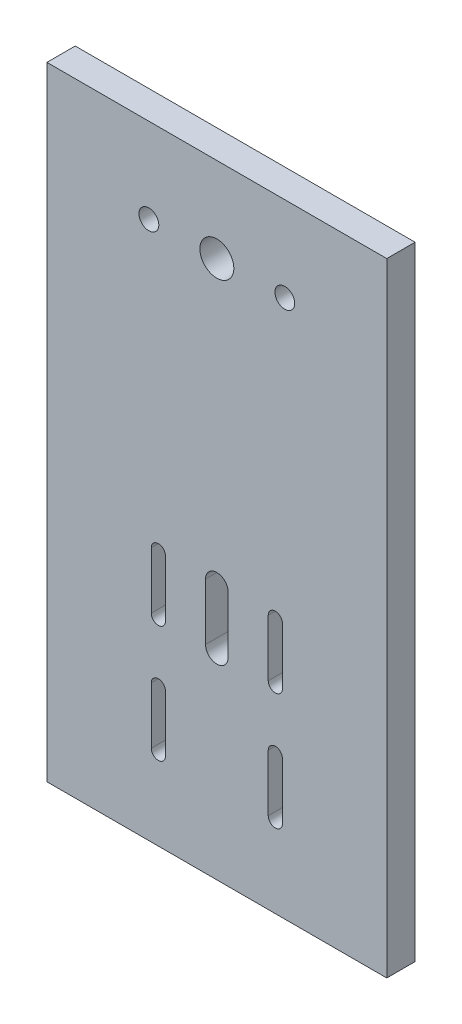
SolidWorks part; units mm, degrees
ref_plane "Front Plane" through (0, 0, 0) normal (0, 0, 1) x (1, 0, 0)
ref_plane "Top Plane" through (0, 0, 0) normal (0, 1, 0) x (1, 0, 0)
ref_plane "Right Plane" through (0, 0, 0) normal (1, 0, 0) x (0, 0, -1)
sketch "Sketch1" plane through (0, 0, 0) normal (0, 0, 1) x (1, 0, 0)
  line L0 (0, 15.2356) -> (0, -145.5963) construction
  line L1 (-60, 15.2356) -> (60, 15.2356)
  line L2 (-60, 15.2356) -> (-60, -204.7644)
  line L3 (-60, -204.7644) -> (60, -204.7644)
  line L4 (60, 15.2356) -> (60, -204.7644)
  line L5 (-60, -94.7644) -> (60, -94.7644) construction
  line L6 (-60, -14.7644) -> (60, -14.7644) construction
  line L7 (0, -114.7644) -> (0, -134.7644) construction
  line L8 (4, -114.7644) -> (4, -134.7644)
  line L9 (-4, -114.7644) -> (-4, -134.7644)
  line L10 (0, -124.7644) -> (157.2119, -124.7644) construction
  line L11 (20.65, -114.7644) -> (20.65, -134.7644) construction
  line L12 (23.15, -114.7644) -> (23.15, -134.7644)
  line L13 (18.15, -114.7644) -> (18.15, -134.7644)
  line L14 (-20.65, -114.7644) -> (-20.65, -134.7644) construction
  line L15 (-23.15, -114.7644) -> (-23.15, -134.7644)
  line L16 (-18.15, -114.7644) -> (-18.15, -134.7644)
  line L17 (-85.4074, -145.4144) -> (104.8908, -145.4144) construction
  line L18 (-20.65, -176.0644) -> (-20.65, -156.0644) construction
  line L19 (-23.15, -176.0644) -> (-23.15, -156.0644)
  line L20 (-18.15, -176.0644) -> (-18.15, -156.0644)
  line L21 (20.65, -176.0644) -> (20.65, -156.0644) construction
  line L22 (23.15, -176.0644) -> (23.15, -156.0644)
  line L23 (18.15, -176.0644) -> (18.15, -156.0644)
  circle A0 centre (0, -14.7644) radius 6
  circle A1 centre (24, -14.7644) radius 3.5
  circle A2 centre (-24, -14.7644) radius 3.5
  arc A3 (4, -114.7644) -> (-4, -114.7644) centre (0, -114.7644) ccw
  arc A4 (-4, -134.7644) -> (4, -134.7644) centre (0, -134.7644) ccw
  arc A5 (23.15, -114.7644) -> (18.15, -114.7644) centre (20.65, -114.7644) ccw
  arc A6 (18.15, -134.7644) -> (23.15, -134.7644) centre (20.65, -134.7644) ccw
  arc A7 (-23.15, -114.7644) -> (-18.15, -114.7644) centre (-20.65, -114.7644) cw
  arc A8 (-18.15, -134.7644) -> (-23.15, -134.7644) centre (-20.65, -134.7644) cw
  arc A9 (-23.15, -176.0644) -> (-18.15, -176.0644) centre (-20.65, -176.0644) ccw
  arc A10 (-18.15, -156.0644) -> (-23.15, -156.0644) centre (-20.65, -156.0644) ccw
  arc A11 (23.15, -176.0644) -> (18.15, -176.0644) centre (20.65, -176.0644) cw
  arc A12 (18.15, -156.0644) -> (23.15, -156.0644) centre (20.65, -156.0644) cw
  point P19 (0, -124.7644)
  point P28 (20.65, -124.7644)
  point P35 (-20.65, -124.7644)
  point P44 (-20.65, -166.0644)
  point P51 (20.65, -166.0644)
  dimension "D4" = 12
  dimension "D5" = 7
  dimension "D6" = 20
  dimension "D7" = 4
  dimension "D12" = 2.5
  dimension "D1" = 120
  dimension "D2" = 220
  dimension "D3" = 30
  dimension "D8" = 80
  dimension "D9" = 30
  dimension "D10" = 110
  dimension "D11" = 20
  dimension "D13" = 20.65
  dimension "D14" = 20.65
  dimension "D15" = 24
extrude "Boss-Extrude1" add sketch "Sketch1" along normal blind 10
